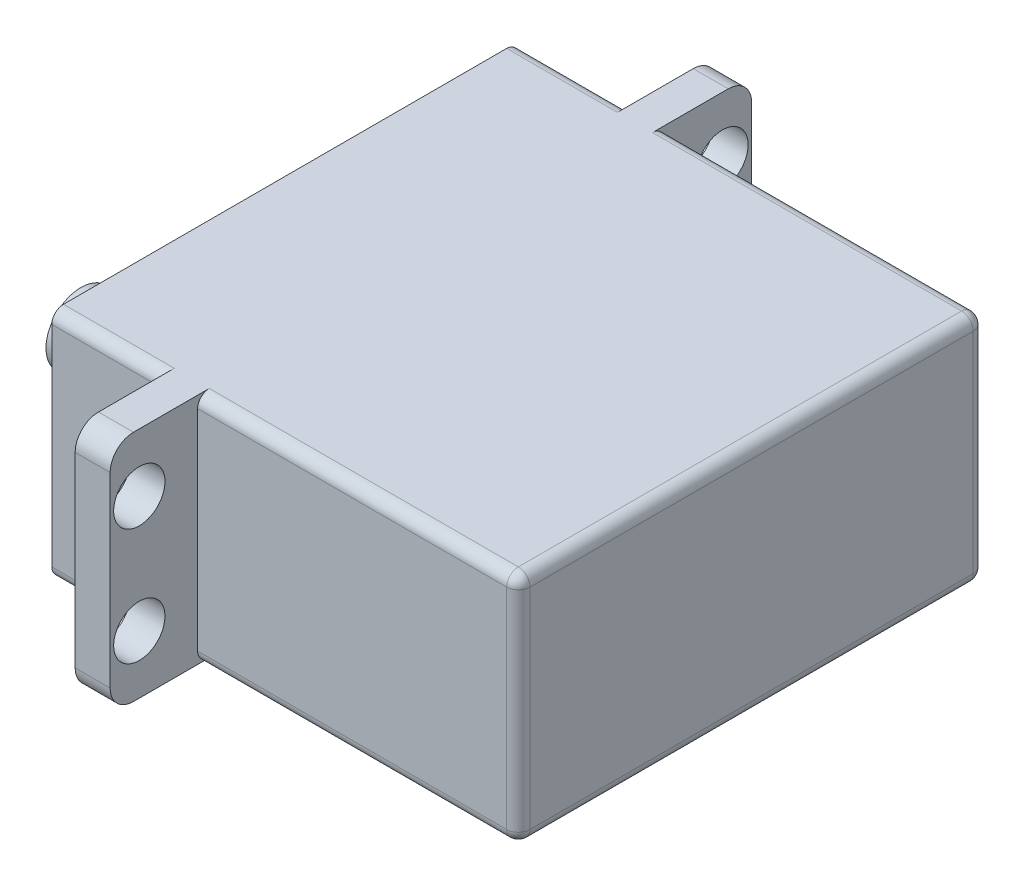
SolidWorks part; units mm, degrees
ref_plane "正面" through (0, 0, 0) normal (0, 0, 1) x (1, 0, 0)
ref_plane "平面" through (0, 0, 0) normal (0, 1, 0) x (1, 0, 0)
ref_plane "右側面" through (0, 0, 0) normal (1, 0, 0) x (0, 0, -1)
sketch "ｽｹｯﾁ1" plane through (0, 0, 0) normal (1, 0, 0) x (0, 0, -1)
  line L0 (0, 0) -> (0, -10)
  line L1 (0, 0) -> (40, 0)
  line L2 (0, 0) -> (0, -20)
  line L3 (0, -20) -> (40, -20)
  line L4 (40, 0) -> (40, -20)
  line L7 (0, 0) -> (-7.25, 0)
  line L8 (55, 0) -> (-55, 0) construction
extrude "ﾎﾞｽ - 押し出し1" add sketch "ｽｹｯﾁ1" along normal blind 27.5 contours L4 L1 L0 L2 L3
sketch "ｽｹｯﾁ2" plane through (0, 0, 0) normal (-1, 0, 0) x (0, 0, 1)
  line L0 (5.5, 0) -> (-45.5, 0)
  line L2 (15.125, 0) -> (-15.125, 0) construction
  line L3 (7.5, -2) -> (7.5, -18)
  line L5 (5.5, -20) -> (-45.5, -20)
  line L6 (-47.5, -2) -> (-47.5, -18)
  circle A1 centre (-45, -5) radius 2.2
  circle A2 centre (5, -5) radius 2.2
  circle A3 centre (5, -15) radius 2.2
  circle A4 centre (-45, -15) radius 2.2
  arc A5 (5.5, -20) -> (7.5, -18) centre (5.5, -18) ccw
  arc A6 (5.5, 0) -> (7.5, -2) centre (5.5, -2) cw
  arc A7 (-47.5, -18) -> (-45.5, -20) centre (-45.5, -18) ccw
  arc A8 (-47.5, -2) -> (-45.5, 0) centre (-45.5, -2) cw
  point P19 (-20, -10)
  point P25 (-47.5, 0)
  dimension "D1" = 2
extrude "ﾎﾞｽ - 押し出し2" add sketch "ｽｹｯﾁ2" along normal blind 3
sketch "ｽｹｯﾁ3" plane through (27.5, 0, 0) normal (1, 0, 0) x (0, 0, -1)
  line L1 (0, 0) -> (40, 0)
  line L2 (0, 0) -> (0, -20)
  line L3 (0, -20) -> (40, -20)
  line L4 (40, 0) -> (40, -20)
extrude "ﾎﾞｽ - 押し出し3" add sketch "ｽｹｯﾁ3" against normal blind 40
ref_plane "平面1" through (-12.5, 0, 0) normal (-1, 0, 0) x (0, 0, 1)
sketch "ｽｹｯﾁ4" plane through (-12.5, 0, 0) normal (-1, 0, 0) x (0, 0, 1)
  line L0 (-40, -20) -> (-10, -20)
  line L1 (0, -20) -> (-40, -20) construction
  line L2 (7.5, -10) -> (-10, -10)
  line L3 (7.5, -18) -> (7.5, -2) construction
  circle A0 centre (-10, -10) radius 3
extrude "ﾎﾞｽ - 押し出し4" add sketch "ｽｹｯﾁ4" along normal blind 7.5
fillet "ﾌｨﾚｯﾄ1" radius 1 12 edges at (27.5, -20, -20) (27.5, -10, -40) (27.5, 0, -20) (-7.75, 0, -40) (-7.75, -20, -40) (13.75, -20, -40) (13.75, 0, -40) (-7.75, 0, 0) (-7.75, -20, 0) (13.75, -20, 0) (27.5, -10, 0) (13.75, 0, 0)
ref_plane "平面2" through (-22.5, 0, 0) normal (-1, 0, 0) x (0, 0, 1)
